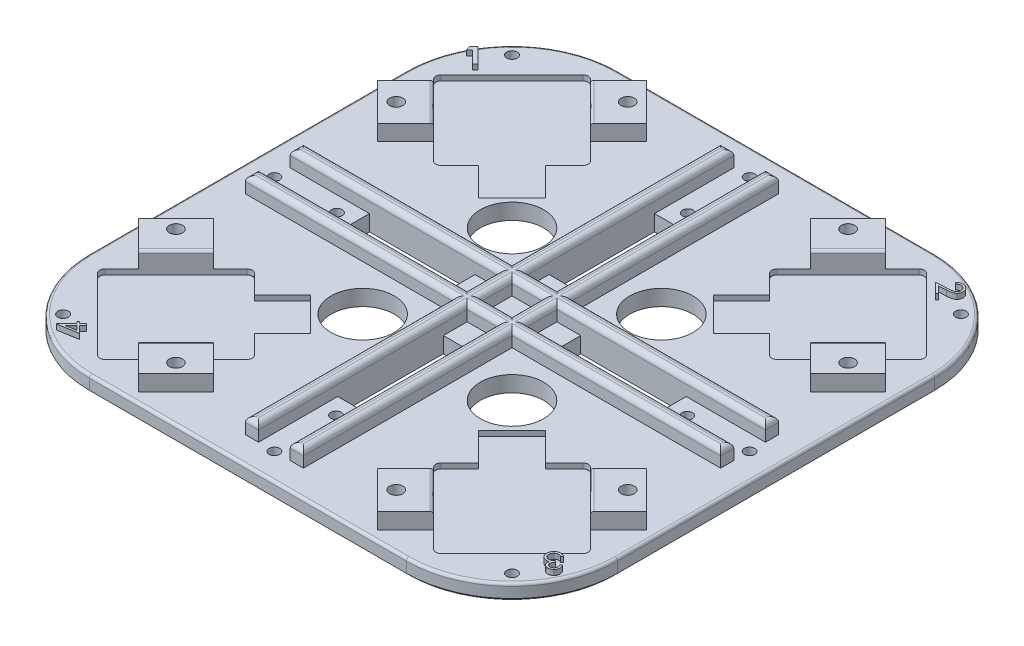
SolidWorks part; units mm, degrees
ref_plane "Спереди" through (0, 0, 0) normal (0, 0, 1) x (1, 0, 0)
ref_plane "Сверху" through (0, 0, 0) normal (0, 1, 0) x (1, 0, 0)
ref_plane "Справа" through (0, 0, 0) normal (1, 0, 0) x (0, 0, -1)
sketch "Эскиз1" plane through (0, 0, 0) normal (0, 1, 0) x (1, 0, 0)
  line L1 (-100, -100) -> (100, -100)
  line L2 (-100, -100) -> (-100, 100)
  line L3 (-100, 100) -> (100, 100)
  line L4 (100, -100) -> (100, 100)
  line L5 (0, 100) -> (0, -100) construction
  line L6 (-100, 0) -> (100, 0) construction
  line L11 (0, 75) -> (0, -75) construction
  line L12 (-39.5, 0) -> (39.5, 0) construction
  line L13 (-85, -85) -> (85, -85) construction
  line L14 (-85, -85) -> (-85, 85) construction
  line L15 (-85, 85) -> (85, 85) construction
  line L16 (85, -85) -> (85, 85) construction
  line L17 (0, 85) -> (0, -85) construction
  line L18 (-85, 0) -> (85, 0) construction
  circle A8 centre (-90, 0) radius 2
  circle A9 centre (0, 90) radius 2
  circle A10 centre (90, 0) radius 2
  circle A11 centre (0, -90) radius 2
  circle A12 centre (-85, 85) radius 2
  circle A13 centre (85, 85) radius 2
  circle A14 centre (85, -85) radius 2
  circle A15 centre (-85, -85) radius 2
  point P0 (0, 0)
  point P4 (0, 0)
  point P5 (0, 0)
  point P11 (0, 0)
  point P27 (0, 0)
  dimension "D6" = 90
  dimension "D1" = 200
  dimension "D8" = 170
  dimension "D7" = 4
extrude "Бобышка-Вытянуть1" add sketch "Эскиз1" along normal blind 6
sketch "Эскиз2" plane through (0, 6, 0) normal (0, 1, 0) x (1, 0, 0)
  line L0 (0, 72.2532) -> (0, 0) construction
  line L1 (0, 0) -> (100, 100) construction
  line L2 (63.6396, 33.9411) -> (33.9411, 63.6396)
  line L3 (63.6396, 33.9411) -> (93.3381, 63.6396)
  line L4 (33.9411, 63.6396) -> (63.6396, 93.3381)
  line L5 (93.3381, 63.6396) -> (63.6396, 93.3381)
  line L6 (63.6396, 33.9411) -> (63.6396, 93.3381) construction
  line L7 (33.9411, 63.6396) -> (93.3381, 63.6396) construction
  line L8 (33.9411, -63.6396) -> (63.6396, -33.9411)
  line L9 (33.9411, -63.6396) -> (63.6396, -93.3381)
  line L10 (63.6396, -93.3381) -> (93.3381, -63.6396)
  line L11 (63.6396, -33.9411) -> (93.3381, -63.6396)
  line L12 (-63.6396, -33.9411) -> (-33.9411, -63.6396)
  line L13 (-63.6396, -33.9411) -> (-93.3381, -63.6396)
  line L14 (-93.3381, -63.6396) -> (-63.6396, -93.3381)
  line L15 (-33.9411, -63.6396) -> (-63.6396, -93.3381)
  line L16 (-33.9411, 63.6396) -> (-63.6396, 33.9411)
  line L17 (-33.9411, 63.6396) -> (-63.6396, 93.3381)
  line L18 (-63.6396, 93.3381) -> (-93.3381, 63.6396)
  line L19 (-63.6396, 33.9411) -> (-93.3381, 63.6396)
  point P6 (63.6396, 63.6396)
  point P24 (0, 0)
  dimension "D1" = 42
  dimension "D2" = 90
  dimension "D3" = 4
extrude "Вырез-Вытянуть1" cut sketch "Эскиз2" against normal blind 2
fillet "Скругление1" radius 2 16 edges at (63.6396, 5, -33.9411) (33.9411, 5, -63.6396) (93.3381, 5, -63.6396) (63.6396, 5, -93.3381) (-63.6396, 5, -93.3381) (-63.6396, 5, -33.9411) (-93.3381, 5, -63.6396) (-33.9411, 5, -63.6396) (63.6396, 5, 93.3381) (93.3381, 5, 63.6396) (63.6396, 5, 33.9411) (33.9411, 5, 63.6396) (-63.6396, 5, 93.3381) (-33.9411, 5, 63.6396) (-63.6396, 5, 33.9411) (-93.3381, 5, 63.6396)
sketch "Эскиз3" plane through (0, 6, 0) normal (0, 1, 0) x (1, 0, 0)
  line L0 (48.7904, 48.7904) -> (67.3817, 67.3817) construction
  line L1 (35.3553, 62.2254) -> (62.2254, 35.3553) construction
  line L2 (48.7904, 78.4889) -> (78.4889, 48.7904) construction
  line L3 (62.2254, 91.9239) -> (35.3553, 65.0538) construction
  line L4 (65.0538, 35.3553) -> (91.9239, 62.2254) construction
  line L5 (41.7193, 71.4178) -> (55.8614, 85.5599)
  line L6 (41.7193, 71.4178) -> (31.1127, 82.0244)
  line L7 (55.8614, 85.5599) -> (45.2548, 96.1665)
  line L8 (31.1127, 82.0244) -> (45.2548, 96.1665)
  line L9 (62.2254, 91.9239) -> (35.3553, 65.0538) construction
  line L10 (85.5599, 55.8614) -> (96.1665, 45.2548)
  line L11 (82.0244, 31.1127) -> (96.1665, 45.2548)
  line L12 (71.4178, 41.7193) -> (82.0244, 31.1127)
  line L13 (71.4178, 41.7193) -> (85.5599, 55.8614)
  line L44 (65.0538, 35.3553) -> (91.9239, 62.2254) construction
  line L45 (0, 128.3294) -> (0, 0) construction
  line L64 (0, 0) -> (145.1139, 0) construction
  line L65 (62.2254, 91.9239) -> (35.3553, 65.0538) construction
  line L90 (48.7904, -78.4889) -> (78.4889, -48.7904) construction
  line L91 (48.7904, -48.7904) -> (67.3817, -67.3817) construction
  line L92 (71.4178, -41.7193) -> (85.5599, -55.8614)
  line L93 (71.4178, -41.7193) -> (82.0244, -31.1127)
  line L94 (82.0244, -31.1127) -> (96.1665, -45.2548)
  line L95 (85.5599, -55.8614) -> (96.1665, -45.2548)
  line L96 (31.1127, -82.0244) -> (45.2548, -96.1665)
  line L97 (55.8614, -85.5599) -> (45.2548, -96.1665)
  line L98 (41.7193, -71.4178) -> (31.1127, -82.0244)
  line L99 (41.7193, -71.4178) -> (55.8614, -85.5599)
  line L100 (-48.7904, -48.7904) -> (-67.3817, -67.3817) construction
  line L101 (-48.7904, -78.4889) -> (-78.4889, -48.7904) construction
  line L102 (-48.7904, 78.4889) -> (-78.4889, 48.7904) construction
  line L103 (-48.7904, 48.7904) -> (-67.3817, 67.3817) construction
  line L104 (-41.7193, -71.4178) -> (-55.8614, -85.5599)
  line L105 (-41.7193, -71.4178) -> (-31.1127, -82.0244)
  line L106 (-55.8614, -85.5599) -> (-45.2548, -96.1665)
  line L107 (-31.1127, -82.0244) -> (-45.2548, -96.1665)
  line L108 (-85.5599, -55.8614) -> (-96.1665, -45.2548)
  line L109 (-82.0244, -31.1127) -> (-96.1665, -45.2548)
  line L110 (-71.4178, -41.7193) -> (-82.0244, -31.1127)
  line L111 (-71.4178, -41.7193) -> (-85.5599, -55.8614)
  line L112 (-71.4178, 41.7193) -> (-85.5599, 55.8614)
  line L113 (-71.4178, 41.7193) -> (-82.0244, 31.1127)
  line L114 (-82.0244, 31.1127) -> (-96.1665, 45.2548)
  line L115 (-85.5599, 55.8614) -> (-96.1665, 45.2548)
  line L116 (-31.1127, 82.0244) -> (-45.2548, 96.1665)
  line L117 (-55.8614, 85.5599) -> (-45.2548, 96.1665)
  line L118 (-41.7193, 71.4178) -> (-31.1127, 82.0244)
  line L119 (-41.7193, 71.4178) -> (-55.8614, 85.5599)
  point P16 (48.7904, 78.4889)
  dimension "D1" = 20
  dimension "D2" = 15
extrude "Бобышка-Вытянуть3" add sketch "Эскиз3" along normal blind 6
fillet "Скругление4" radius 40 4 edges at (100, 3, -100) (100, 3, 100) (-100, 3, 100) (-100, 3, -100)
sketch "Эскиз4" plane through (0, 12, 0) normal (0, 1, 0) x (1, 0, 0)
  line L0 (89.0955, 38.1838) -> (38.1838, 89.0955) construction
  line L1 (82.0244, 31.1127) -> (96.1665, 45.2548) construction
  line L2 (45.2548, 96.1665) -> (31.1127, 82.0244) construction
  line L3 (41.7193, 71.4178) -> (55.8614, 85.5599) construction
  line L4 (48.7904, 48.7904) -> (78.4889, 78.4889) construction
  line L5 (35.3553, 62.2254) -> (62.2254, 35.3553) construction
  line L6 (91.9239, 65.0538) -> (65.0538, 91.9239) construction
  line L7 (0, 119.2498) -> (0, 0) construction
  line L8 (0, 0) -> (156.895, 0) construction
  line L9 (48.7904, -48.7904) -> (78.4889, -78.4889) construction
  line L10 (89.0955, -38.1838) -> (38.1838, -89.0955) construction
  line L11 (-89.0955, -38.1838) -> (-38.1838, -89.0955) construction
  line L12 (-48.7904, -48.7904) -> (-78.4889, -78.4889) construction
  line L13 (-48.7904, 48.7904) -> (-78.4889, 78.4889) construction
  line L14 (-89.0955, 38.1838) -> (-38.1838, 89.0955) construction
  circle A0 centre (41.7193, 85.5599) radius 2.5
  circle A1 centre (85.5599, 41.7193) radius 2.5
  circle A14 centre (85.5599, -41.7193) radius 2.5
  circle A15 centre (41.7193, -85.5599) radius 2.5
  circle A16 centre (-41.7193, -85.5599) radius 2.5
  circle A17 centre (-85.5599, -41.7193) radius 2.5
  circle A18 centre (-85.5599, 41.7193) radius 2.5
  circle A19 centre (-41.7193, 85.5599) radius 2.5
  dimension "D1" = 10
  dimension "D3" = 62
extrude "Вырез-Вытянуть2" cut sketch "Эскиз4" against normal blind 8
sketch "Эскиз5" plane through (0, 6, 0) normal (0, 1, 0) x (1, 0, 0)
  line L0 (0, 85.0414) -> (0, -87.3859) construction
  line L1 (-6, 90) -> (-11, 90)
  line L2 (111.3105, 0) -> (-132.9438, 0) construction
  line L3 (6, -90) -> (11, -90)
  line L4 (6, -90) -> (6, 90)
  line L5 (6, 90) -> (11, 90)
  line L6 (11, -90) -> (11, 90)
  line L7 (8.5, 90) -> (8.5, -90) construction
  line L8 (6, 0) -> (11, 0) construction
  line L9 (-11, -90) -> (-11, 90)
  line L10 (-6, -90) -> (-11, -90)
  line L11 (-6, -90) -> (-6, 90)
  line L12 (-6, 0) -> (-11, 0) construction
  line L13 (-8.5, 90) -> (-8.5, -90) construction
  point P3 (8.5, 0)
  point P13 (-8.5, 0)
  dimension "D1" = 5
  dimension "D2" = 180
  dimension "D3" = 12
extrude "Бобышка-Вытянуть4" add sketch "Эскиз5" along normal blind 6
sketch "Эскиз6" plane through (0, 6, 0) normal (0, 1, 0) x (1, 0, 0)
  line L0 (-101.5062, 0) -> (110.1382, 0) construction
  line L1 (-90, -8.5) -> (90, -8.5) construction
  line L2 (-90, 11) -> (90, 11)
  line L3 (-90, 11) -> (-90, 6)
  line L4 (-90, 6) -> (90, 6)
  line L5 (90, 11) -> (90, 6)
  line L6 (0, 6) -> (0, 11) construction
  line L7 (-90, 8.5) -> (90, 8.5) construction
  line L8 (0, -6) -> (0, -11) construction
  line L9 (90, -11) -> (90, -6)
  line L10 (-90, -6) -> (90, -6)
  line L11 (-90, -11) -> (-90, -6)
  line L12 (-90, -11) -> (90, -11)
  point P3 (0, 8.5)
  point P15 (0, -8.5)
  dimension "D1" = 180
  dimension "D2" = 5
  dimension "D3" = 12
extrude "Бобышка-Вытянуть5" add sketch "Эскиз6" along normal blind 6
fillet "Скругление5" radius 2 32 edges at (-8.5, 12, 90) (-11, 12, -50.5) (-11, 12, 50.5) (-8.5, 12, -90) (-6, 12, -50.5) (-6, 12, 50.5) (8.5, 12, 90) (6, 12, 50.5) (6, 12, -50.5) (8.5, 12, -90) (11, 12, 50.5) (11, 12, -50.5) (0, 12, -6) (-6, 12, 0) (0, 12, 6) (6, 12, 0) (-50.5, 12, 11) (-90, 12, 8.5) (-50.5, 12, 6) (-11, 12, 0) (-50.5, 12, -6) (-90, 12, -8.5) (-50.5, 12, -11) (0, 12, -11) (50.5, 12, -11) (90, 12, -8.5) (50.5, 12, -6) (11, 12, 0) (50.5, 12, 6) (90, 12, 8.5) (50.5, 12, 11) (0, 12, 11)
sketch "Эскиз7" plane through (0, 6, 0) normal (0, 1, 0) x (1, 0, 0)
  line L0 (0, 76.3028) -> (0, 0) construction
  line L1 (0, 0) -> (74.3797, 74.3797) construction
  line L2 (20, 6) -> (60, 6)
  line L3 (-6, 20) -> (6, 20)
  line L4 (-6, 20) -> (-6, 60)
  line L5 (-6, 60) -> (6, 60)
  line L6 (6, 20) -> (6, 60)
  line L7 (0, 60) -> (0, 20) construction
  line L8 (-6, 40) -> (6, 40) construction
  line L9 (20, 6) -> (20, -6)
  line L10 (20, -6) -> (60, -6)
  line L11 (60, 6) -> (60, -6)
  line L12 (6, -20) -> (6, -60)
  line L13 (6, -20) -> (-6, -20)
  line L14 (-6, -20) -> (-6, -60)
  line L15 (6, -60) -> (-6, -60)
  line L16 (-20, -6) -> (-60, -6)
  line L17 (-20, -6) -> (-20, 6)
  line L18 (-20, 6) -> (-60, 6)
  line L19 (-60, -6) -> (-60, 6)
  circle A0 centre (28.2843, 28.2843) radius 12
  circle A1 centre (28.2843, -28.2843) radius 12
  circle A2 centre (-28.2843, -28.2843) radius 12
  circle A3 centre (-28.2843, 28.2843) radius 12
  point P6 (0, 40)
  point P15 (0, 0)
  point P32 (0, 0)
  dimension "D1" = 40
  dimension "D2" = 24
  dimension "D4" = 12
  dimension "D5" = 40
  dimension "D6" = 40
  dimension "D3" = 4
  dimension "D7" = 4
extrude "Вырез-Вытянуть3" cut sketch "Эскиз7" against normal blind 6
sketch "Эскиз8" plane through (0, 6, 0) normal (0, 1, 0) x (1, 0, 0)
  line L0 (48.7904, 48.7904) -> (72.3205, 72.3205) construction
  line L1 (35.3553, 62.2254) -> (62.2254, 35.3553) construction
  line L2 (44.5477, 31.8198) -> (31.8198, 44.5477)
  line L3 (44.5477, 31.8198) -> (65.7609, 53.033)
  line L4 (31.8198, 44.5477) -> (53.033, 65.7609)
  line L5 (65.7609, 53.033) -> (53.033, 65.7609)
  line L6 (44.5477, 31.8198) -> (53.033, 65.7609) construction
  line L7 (31.8198, 44.5477) -> (65.7609, 53.033) construction
  line L20 (0, 107.5006) -> (0, 0) construction
  line L21 (0, 0) -> (140.6034, 0) construction
  line L22 (31.8198, -44.5477) -> (65.7609, -53.033) construction
  line L23 (44.5477, -31.8198) -> (53.033, -65.7609) construction
  line L24 (48.7904, -48.7904) -> (72.3205, -72.3205) construction
  line L25 (65.7609, -53.033) -> (53.033, -65.7609)
  line L26 (31.8198, -44.5477) -> (53.033, -65.7609)
  line L27 (44.5477, -31.8198) -> (65.7609, -53.033)
  line L28 (44.5477, -31.8198) -> (31.8198, -44.5477)
  line L29 (-48.7904, -48.7904) -> (-72.3205, -72.3205) construction
  line L30 (-44.5477, -31.8198) -> (-53.033, -65.7609) construction
  line L31 (-31.8198, -44.5477) -> (-65.7609, -53.033) construction
  line L32 (-31.8198, 44.5477) -> (-65.7609, 53.033) construction
  line L33 (-44.5477, 31.8198) -> (-53.033, 65.7609) construction
  line L34 (-48.7904, 48.7904) -> (-72.3205, 72.3205) construction
  line L35 (-44.5477, -31.8198) -> (-31.8198, -44.5477)
  line L36 (-44.5477, -31.8198) -> (-65.7609, -53.033)
  line L37 (-31.8198, -44.5477) -> (-53.033, -65.7609)
  line L38 (-65.7609, -53.033) -> (-53.033, -65.7609)
  line L39 (-65.7609, 53.033) -> (-53.033, 65.7609)
  line L40 (-31.8198, 44.5477) -> (-53.033, 65.7609)
  line L41 (-44.5477, 31.8198) -> (-65.7609, 53.033)
  line L42 (-44.5477, 31.8198) -> (-31.8198, 44.5477)
  point P24 (0, 16.9706)
  dimension "D1" = 18
  dimension "D2" = 30
extrude "Вырез-Вытянуть4" cut sketch "Эскиз8" against normal blind 2 contours L2 L3 L5 L4
fillet "Скругление6" radius 1 8 edges at (78.4889, 12, -48.7904) (48.7904, 12, -78.4889) (-78.4889, 12, 48.7904) (-48.7904, 12, 78.4889) (48.7904, 12, 78.4889) (78.4889, 12, 48.7904) (-78.4889, 12, -48.7904) (-48.7904, 12, -78.4889)
sketch "Эскиз9" plane through (0, 6, 0) normal (0, 1, 0) x (1, 0, 0)
  line L0 (-70.7105, 0.151) -> (0.151, 70.7105) construction
  line L1 (-70.7105, 0.151) -> (-0.151, -70.7105) construction
  line L2 (0.151, 70.7105) -> (70.7105, -0.151) construction
  line L3 (-0.151, -70.7105) -> (70.7105, -0.151) construction
  line L4 (-70.7105, 0.151) -> (70.7105, -0.151) construction
  line L5 (0.151, 70.7105) -> (-0.151, -70.7105) construction
  line L6 (0, 0) -> (60.8554, 60.8554) construction
  circle A0 centre (0.1419, 66.4679) radius 2
  circle A4 centre (-0.1419, -66.4679) radius 2
  circle A5 centre (66.4679, -0.1419) radius 2
  circle A6 centre (-66.4679, 0.1419) radius 2
  point P1 (0, 0)
  dimension "D2" = 4
  dimension "D3" = 3
  dimension "D4" = 3
  dimension "D5" = 94
  dimension "D1" = 100
extrude "Вырез-Вытянуть5" cut sketch "Эскиз9" against normal blind 10
sketch "Эскиз10" plane through (0, 6, 0) normal (0, 1, 0) x (1, 0, 0)
  line L0 (-89.4334, 70.8427) -> (-83.9454, 76.3307) construction
  line L1 (0, 108.5259) -> (0, 0) construction
  line L2 (71.3984, 88.9173) -> (76.8147, 83.501) construction
  line L3 (90.0364, -69.9365) -> (84.274, -75.6989) construction
  line L4 (-72.0522, -89.0668) -> (-79.6906, -81.6618) construction
  text T0 "<b>1</b>" font "Century Gothic" height 8
  text T1 "2" font "Century Gothic" height 8
  text T2 "3" font "Century Gothic" height 8
  text T3 "4" font "Century Gothic" height 8
  point P11 (0, 0)
  point P13 (-78.6721, -82.5954)
  point P14 (-79.2026, -81.6831)
  point P15 (-69.6758, -91.2098)
  point P16 (-79.6906, -81.6618)
  point P17 (-72.0522, -89.0668)
extrude "Бобышка-Вытянуть6" add sketch "Эскиз10" along normal blind 2
fillet "Скругление9" radius 1 8 edges at (88.2843, 6, 88.2843) (0, 6, 100) (-88.2843, 6, 88.2843) (-100, 6, 0) (-88.2843, 6, -88.2843) (0, 6, -100) (88.2843, 6, -88.2843) (100, 6, 0)
chamfer "Фаска1" distance 1 angle 45 8 edges at (100, 0, 0) (88.2843, 0, -88.2843) (88.2843, 0, 88.2843) (0, 0, -100) (0, 0, 100) (-88.2843, 0, -88.2843) (-88.2843, 0, 88.2843) (-100, 0, 0)
